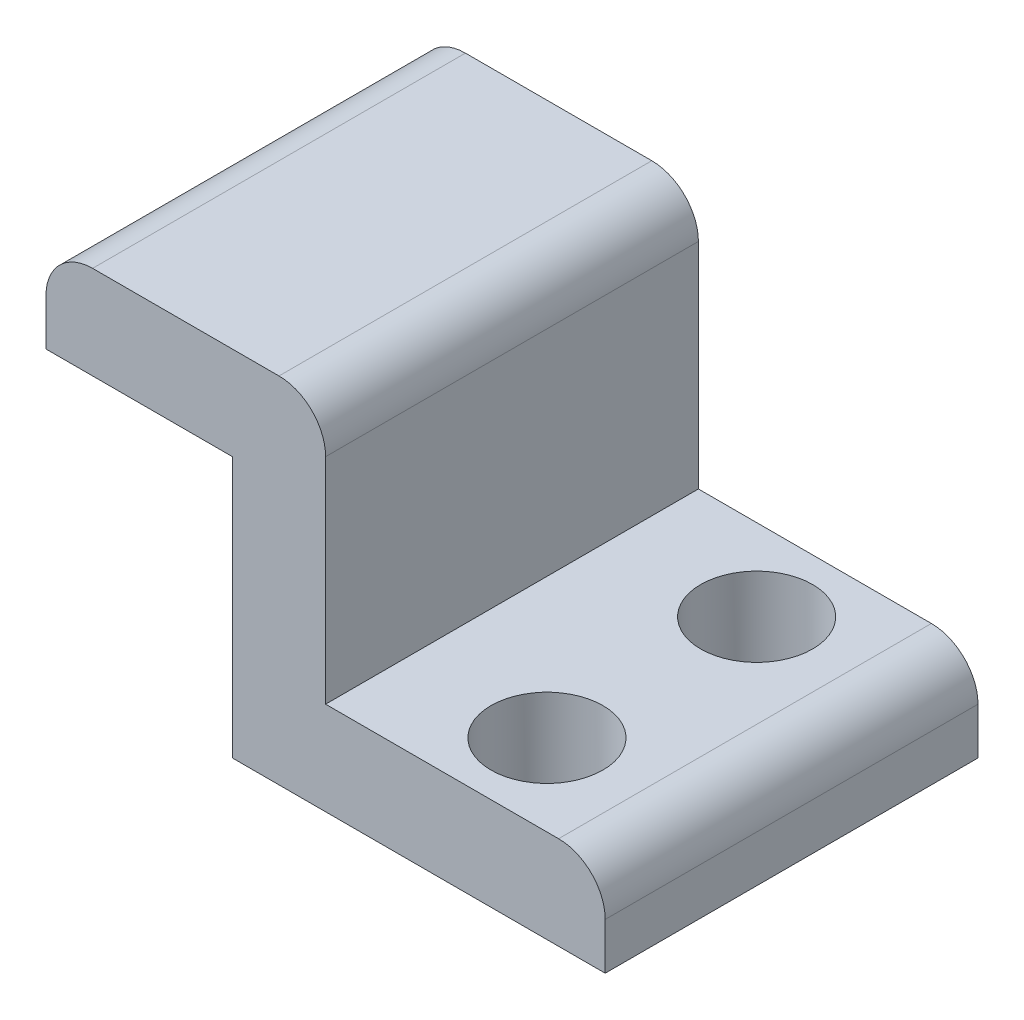
SolidWorks part; units mm, degrees
ref_plane "Front Plane" through (0, 0, 0) normal (0, 0, 1) x (1, 0, 0)
ref_plane "Top Plane" through (0, 0, 0) normal (0, 1, 0) x (1, 0, 0)
ref_plane "Right Plane" through (0, 0, 0) normal (1, 0, 0) x (0, 0, -1)
sketch "Sketch1" plane through (0, 0, 0) normal (0, 0, 1) x (1, 0, 0)
  line L0 (0, 0) -> (8, 0)
  line L1 (55, 0) -> (-55, 0) construction
  line L2 (8, 0) -> (8, 1)
  line L3 (7, 2) -> (2, 2)
  line L4 (2, 2) -> (2, 6.6)
  line L5 (1, 7.6) -> (-3, 7.6)
  line L6 (-4, 6.6) -> (-4, 5.6)
  line L7 (-4, 5.6) -> (0, 5.6)
  line L8 (0, -55) -> (0, 55) construction
  line L9 (0, 5.6) -> (0, 0)
  line L10 (0, 3.3245) -> (2, 3.3245) construction
  line L11 (-3.075, 7.6) -> (-3.075, 5.6) construction
  line L12 (3.5544, 2) -> (3.5544, 0) construction
  arc A0 (8, 1) -> (7, 2) centre (7, 1) ccw
  arc A1 (2, 6.6) -> (1, 7.6) centre (1, 6.6) ccw
  arc A3 (-3, 7.6) -> (-4, 6.6) centre (-3, 6.6) ccw
  point P26 (2, 2)
  dimension "D4" = 5
  dimension "D3" = 1
  dimension "D5" = 4
  dimension "D1" = 5.6
  dimension "D2" = 2
extrude "Boss-Extrude1" add sketch "Sketch1" along normal blind 8
ref_plane "Plane1" through (0, 12, 0) normal (0, 1, 0) x (1, 0, 0)
hole_wizard "M2 Clearance Hole2" positions "Sketch2" profile "Sketch3" hole size "M2" standard "ANSI Metric" end condition through all
sketch "Sketch2" plane through (0, 12, 0) normal (0, 1, 0) x (1, 0, 0)
  line L8 (8, 0) -> (0, 0)
  line L9 (8, -8) -> (8, 0)
  line L10 (0, -8) -> (8, -8)
  line L11 (0, 0) -> (0, -8)
  line L12 (8, 0) -> (2, 0)
  line L13 (8, -8) -> (8, 0)
  line L14 (2, -8) -> (8, -8)
  line L16 (5, 0) -> (5, -1.75) construction
  line L36 (2, -8) -> (2, 0) construction
  line L37 (2, -8) -> (2, 0)
  point P0 (5, -1.75)
  dimension "D2" = 1.75
  dimension "D1" = 0
sketch "Sketch3" plane through (5, 12, 1.75) normal (1, 0, 0) x (0, 0, 1)
  line L0 (0, 0) -> (0, 12)
  line L1 (0, 12) -> (1.2, 12)
  line L2 (1.2, 12) -> (1.2, 0)
  line L5 (1.2, 0) -> (0, 0)
  line L11 (0, -6.35) -> (0, 107.95) construction
  dimension "Thru Hole Dia." = 2.4
  dimension "Thru Hole Depth" = 12
hole_wizard "M2 Clearance Hole1" positions "Sketch4" profile "Sketch5" hole size "M2" standard "ANSI Metric" end condition through all
sketch "Sketch4" plane through (0, 12, 0) normal (0, 1, 0) x (1, 0, 0)
  line L9 (8, 0) -> (0, 0)
  line L10 (8, -8) -> (8, 0)
  line L11 (0, -8) -> (8, -8)
  line L12 (0, 0) -> (0, -8)
  line L13 (8, 0) -> (2, 0)
  line L14 (8, -8) -> (8, 0)
  line L15 (2, -8) -> (8, -8)
  line L19 (5, -6.25) -> (5, -8) construction
  line L65 (2, -8) -> (2, 0) construction
  line L66 (2, -8) -> (2, 0)
  point P0 (5, -6.25)
  dimension "D2" = 1.75
  dimension "D1" = 0
sketch "Sketch5" plane through (5, 12, 6.25) normal (1, 0, 0) x (0, 0, 1)
  line L0 (0, 0) -> (0, 12)
  line L1 (0, 12) -> (1.2, 12)
  line L2 (1.2, 12) -> (1.2, 0)
  line L5 (1.2, 0) -> (0, 0)
  line L11 (0, -6.35) -> (0, 107.95) construction
  dimension "Thru Hole Dia." = 2.4
  dimension "Thru Hole Depth" = 12
sketch "Sketch6" plane through (0, 0, 0) normal (0, 0, -1) x (-1, 0, 0)
  line L0 (-2, 2) -> (-2, 6.6) construction
  line L1 (8.6866, 11.5255) -> (-2, 11.5255)
  line L2 (8.6866, 11.5255) -> (8.6866, -5.2781)
  line L3 (8.6866, -5.2781) -> (-2, -5.2781)
  line L4 (-2, 11.5255) -> (-2, -5.2781)
extrude "Cut-Extrude1" [suppressed] cut sketch "Sketch6" against normal blind 6.5
